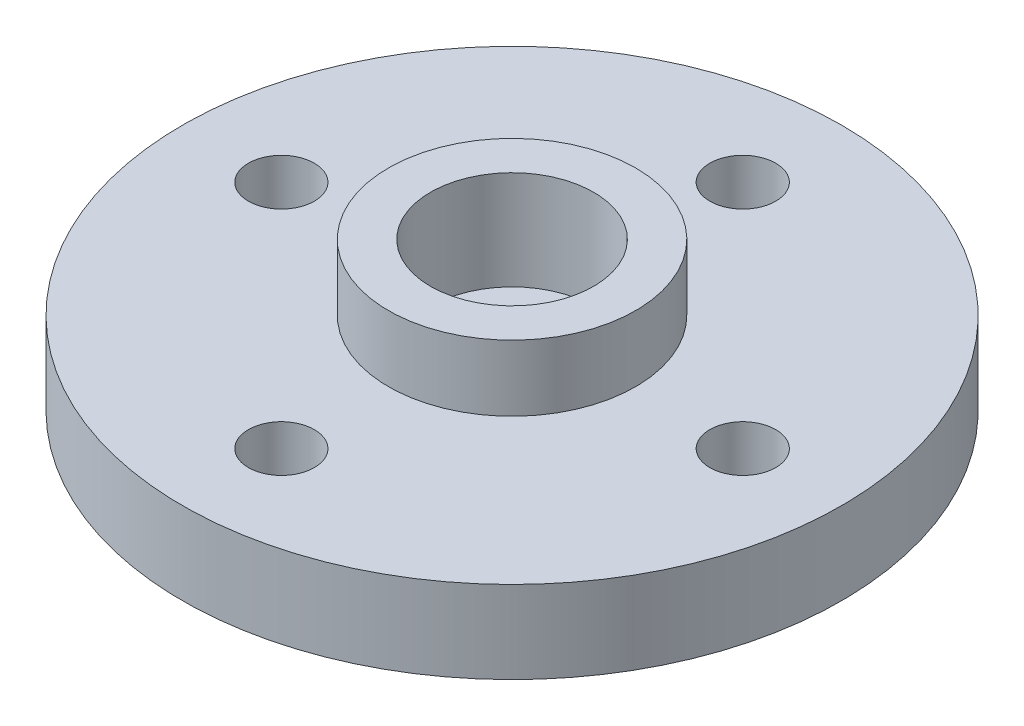
SolidWorks part; units mm, degrees
ref_plane "前视基准面" through (0, 0, 0) normal (0, 0, 1) x (1, 0, 0)
ref_plane "上视基准面" through (0, 0, 0) normal (0, 1, 0) x (1, 0, 0)
ref_plane "右视基准面" through (0, 0, 0) normal (1, 0, 0) x (0, 0, -1)
other "Configuration Table"
sketch "草图1" plane through (0, 0, 0) normal (0, 0, 1) x (1, 0, 0)
  line L0 (0, 0) -> (0, 15.2307) construction
  line L1 (0, 0) -> (10, 0)
  line L2 (10, 0) -> (10, 2.5)
  line L3 (10, 2.5) -> (3.75, 2.5)
  line L4 (3.75, 2.5) -> (3.75, 4.5)
  line L5 (3.75, 4.5) -> (0, 4.5)
  line L6 (0, 4.5) -> (0, 0)
  dimension "D1" = 10
  dimension "D2" = 3.75
  dimension "D3" = 2
  dimension "D4" = 2.5
revolve "旋转1" add sketch "草图1" angle 360 about L0
sketch "草图2" plane through (0, 4.5, 0) normal (0, 1, 0) x (1, 0, 0)
  circle A0 centre (0, 0) radius 1.2
  dimension "D1" = 2.4
extrude "切除-拉伸1" cut sketch "草图2" against normal blind 10
sketch "草图3" plane through (0, 4.5, 0) normal (0, 1, 0) x (1, 0, 0)
  circle A0 centre (0, 0) radius 2.475
  dimension "D1" = 4.95
extrude "切除-拉伸2" cut sketch "草图3" against normal blind 3
sketch "草图4" plane through (0, 0, 0) normal (0, -1, 0) x (1, 0, 0)
  line L0 (0, 0) -> (14.4359, 0) construction
  circle A0 centre (7, 0) radius 1
  circle A1 centre (0, -7) radius 1
  circle A2 centre (-7, 0) radius 1
  circle A3 centre (0, 7) radius 1
  point P5 (-8.8793, -0.4881)
  point P14 (0, 0)
  dimension "D1" = 2
  dimension "D3" = 14
  dimension "D2" = 4
extrude "切除-拉伸3" cut sketch "草图4" against normal blind 3
